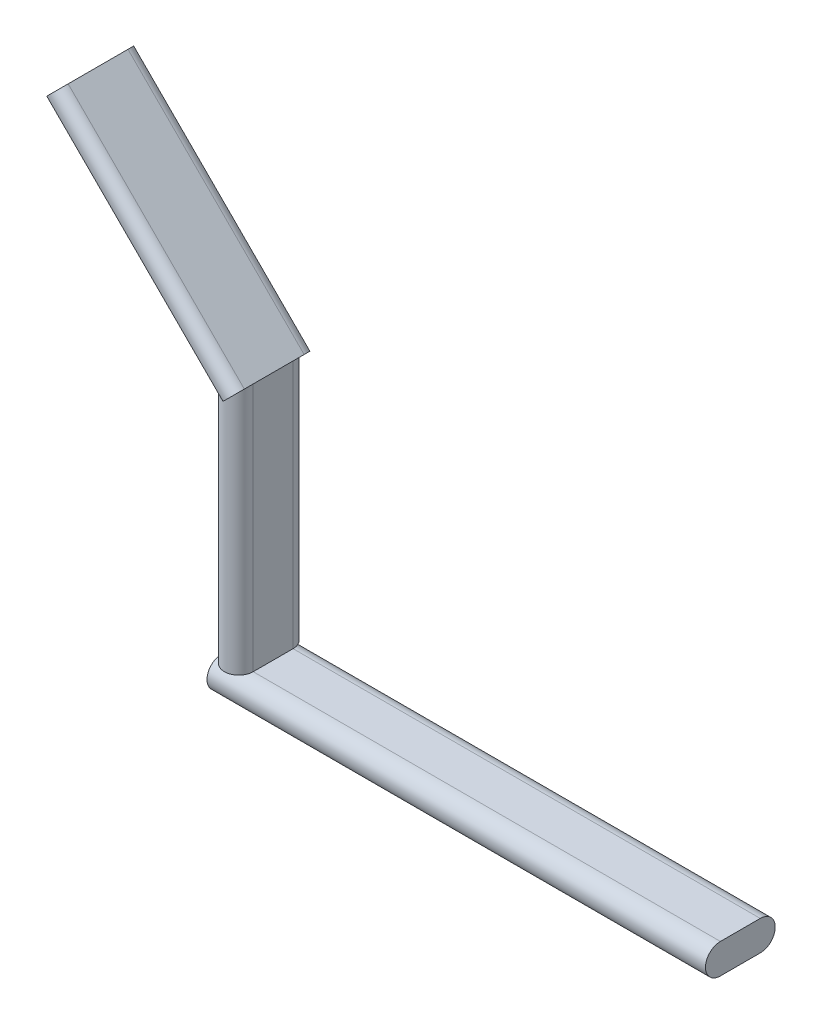
SolidWorks part; units mm, degrees
ref_plane "Front Plane" through (0, 0, 0) normal (0, 0, 1) x (1, 0, 0)
ref_plane "Top Plane" through (0, 0, 0) normal (0, 1, 0) x (1, 0, 0)
ref_plane "Right Plane" through (0, 0, 0) normal (1, 0, 0) x (0, 0, -1)
sketch "Sketch1" plane through (0, 0, 0) normal (1, 0, 0) x (0, 0, -1)
  line L0 (-10, 0) -> (10, 0) construction
  line L1 (-10, 7.5) -> (10, 7.5)
  line L2 (-10, -7.5) -> (10, -7.5)
  arc A0 (-10, 7.5) -> (-10, -7.5) centre (-10, 0) ccw
  arc A1 (10, -7.5) -> (10, 7.5) centre (10, 0) ccw
  point P2 (0, 0)
  dimension "D1" = 15
  dimension "D2" = 20
extrude "Boss-Extrude1" add sketch "Sketch1" along normal blind 250
sketch "Sketch11" plane through (0, 7.5, 0) normal (0, 1, 0) x (1, 0, 0)
  line L0 (8.4471, -10) -> (8.4471, 10) construction
  line L1 (250, -10) -> (0, -10) construction
  line L2 (250, 10) -> (0, 10) construction
  line L3 (1.2208, -10) -> (1.2208, 10)
  line L4 (15.6733, -10) -> (15.6733, 10)
  line L5 (0, 10) -> (0, -10) construction
  line L6 (8.4471, 0) -> (0, 0) construction
  arc A0 (1.2208, -10) -> (15.6733, -10) centre (8.4471, -10) ccw
  arc A1 (15.6733, 10) -> (1.2208, 10) centre (8.4471, 10) ccw
  point P6 (8.4471, 0)
extrude "Boss-Extrude6" add sketch "Sketch11" along normal blind 125
ref_plane "Plane2" through (-58.4133, 58.4133, 0) normal (0.7071, -0.7071, 0) x (-0.7071, -0.7071, 0)
sketch "Sketch12" plane through (-58.4133, 58.4133, 0) normal (0.7071, -0.7071, 0) x (-0.7071, -0.7071, 0)
  line L0 (-100.0226, -15) -> (-100.0226, 15) construction
  line L1 (-105.5681, -15) -> (-105.5681, 15)
  line L2 (-94.477, -15) -> (-94.477, 15)
  line L3 (0, 0) -> (-100.0226, 0) construction
  arc A0 (-105.5681, -15) -> (-94.477, -15) centre (-100.0226, -15) ccw
  arc A1 (-94.477, 15) -> (-105.5681, 15) centre (-100.0226, 15) ccw
  point P2 (-100.0226, 0)
  dimension "D1" = 15
extrude "Boss-Extrude7" add sketch "Sketch12" against normal blind 125
